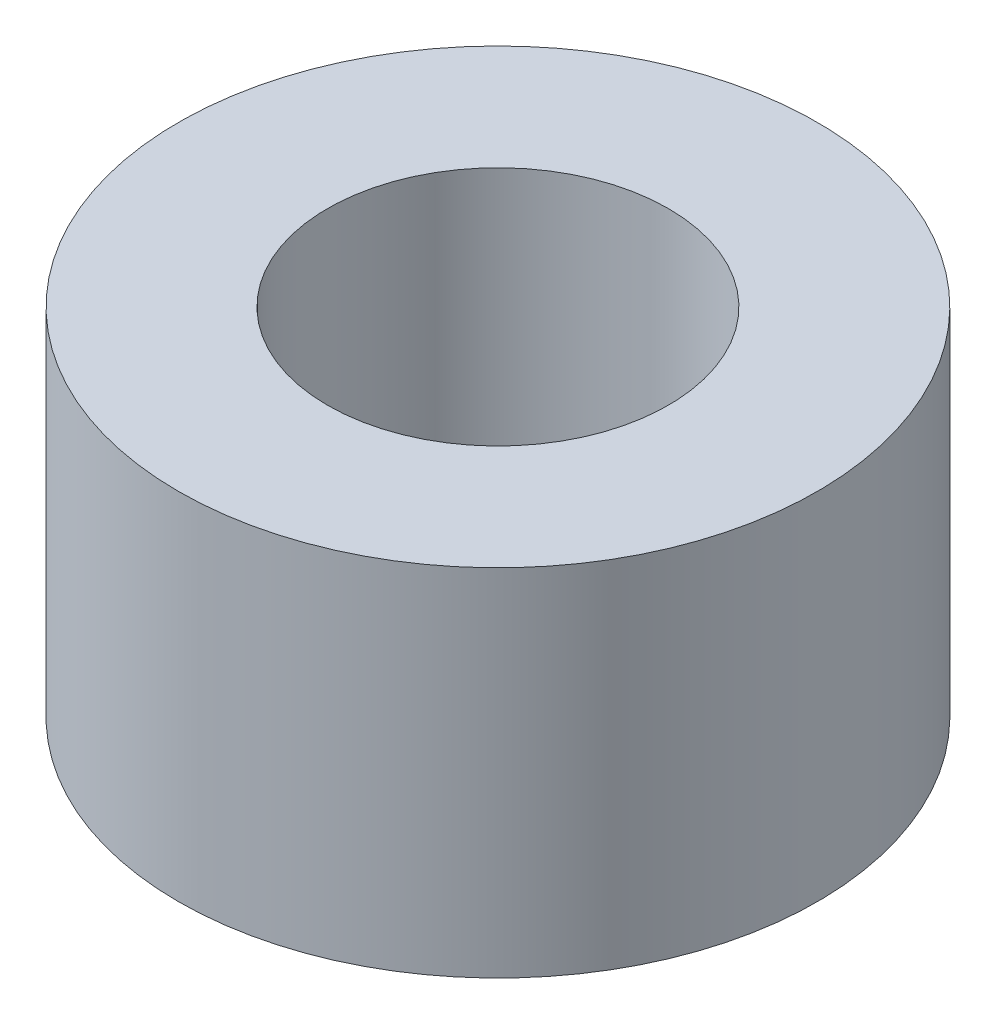
SolidWorks part; units mm, degrees
material "1060 합금"
ref_plane "정면" through (0, 0, 0) normal (0, 0, 1) x (1, 0, 0)
ref_plane "윗면" through (0, 0, 0) normal (0, 1, 0) x (1, 0, 0)
ref_plane "우측면" through (0, 0, 0) normal (1, 0, 0) x (0, 0, -1)
sketch "스케치1" plane through (0, 0, 0) normal (0, 1, 0) x (1, 0, 0)
  circle A0 centre (0, 0) radius 7.5
  dimension "D1" = 15
extrude "보스-돌출1" add sketch "스케치1" against normal blind 8.34
sketch "스케치3" plane through (0, 0, 0) normal (0, 1, 0) x (1, 0, 0)
  circle A0 centre (0, 0) radius 4
  dimension "D1" = 8
extrude "컷-돌출1" cut sketch "스케치3" against normal blind 21.36
